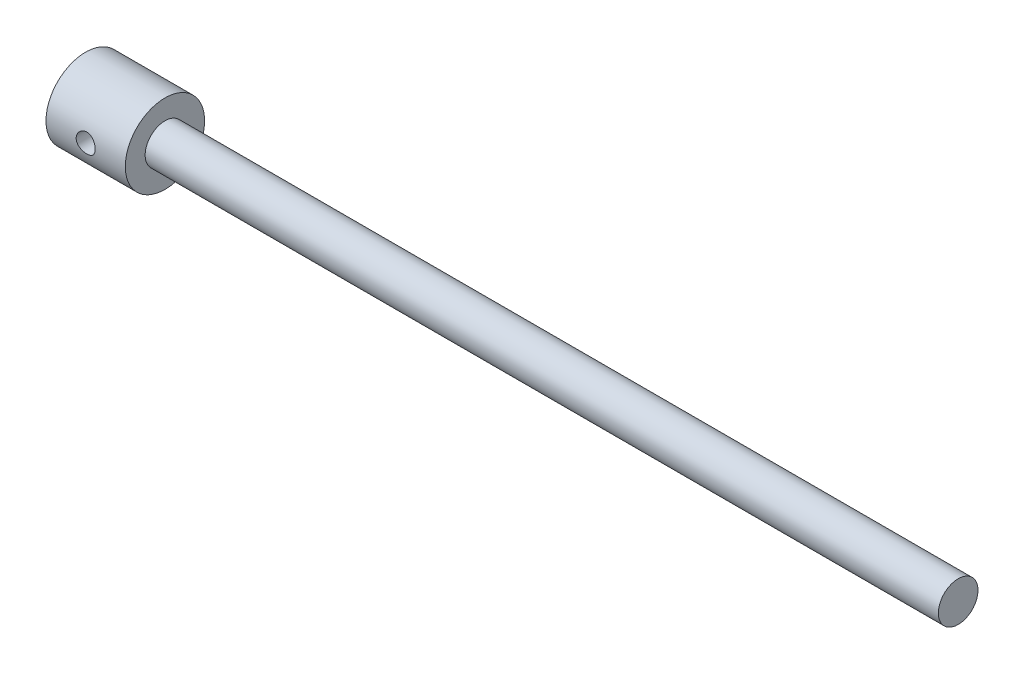
SolidWorks part; units mm, degrees
ref_plane "Front Plane" through (0, 0, 0) normal (0, 0, 1) x (1, 0, 0)
ref_plane "Top Plane" through (0, 0, 0) normal (0, 1, 0) x (1, 0, 0)
ref_plane "Right Plane" through (0, 0, 0) normal (1, 0, 0) x (0, 0, -1)
sketch "Sketch2" plane through (0, 0, 0) normal (1, 0, 0) x (0, 0, -1)
  circle A0 centre (0, 0) radius 12.5
  dimension "D1" = 25
extrude "Boss-Extrude1" add sketch "Sketch2" along normal mid plane 550
sketch "Sketch3" plane through (-275, 0, 0) normal (-1, 0, 0) x (0, 0, 1)
  circle A0 centre (0, 0) radius 25
  dimension "D1" = 50
extrude "Boss-Extrude2" add sketch "Sketch3" against normal blind 50
ref_plane "Plane1" through (0, 0, 30) normal (0, 0, 1) x (1, 0, 0)
sketch "Sketch4" plane through (0, 0, 30) normal (0, 0, 1) x (1, 0, 0)
  line L0 (-275, 25) -> (-275, -25) construction
  circle A0 centre (-250, 0) radius 6
  point P4 (0, 0)
  dimension "D1" = 12
  dimension "D2" = 25
extrude "Cut-Extrude1" cut sketch "Sketch4" against normal through all
